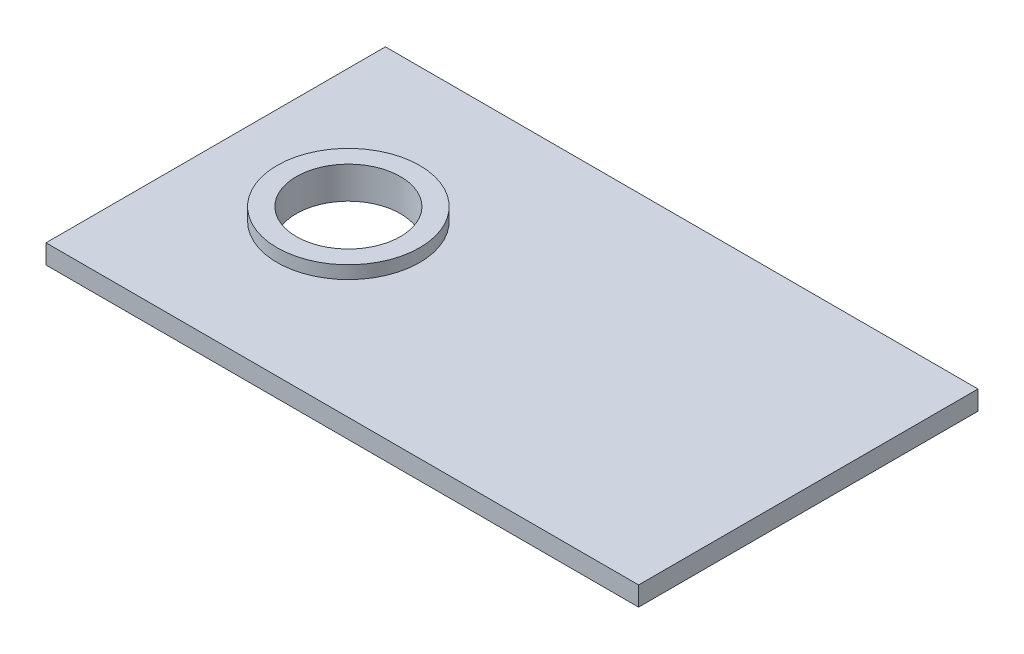
SolidWorks part; units mm, degrees
ref_plane "Front Plane" through (0, 0, 0) normal (0, 0, 1) x (1, 0, 0)
ref_plane "Top Plane" through (0, 0, 0) normal (0, 1, 0) x (1, 0, 0)
ref_plane "Right Plane" through (0, 0, 0) normal (1, 0, 0) x (0, 0, -1)
sketch "Sketch1" plane through (0, 0, 0) normal (0, 1, 0) x (1, 0, 0)
  line L0 (0, 0) -> (-25089.3372, 0) construction
  line L1 (-46.1264, -26.4178) -> (46.1264, -26.4178)
  line L2 (-46.1264, -26.4178) -> (-46.1264, 26.4178)
  line L3 (-46.1264, 26.4178) -> (46.1264, 26.4178)
  line L4 (46.1264, -26.4178) -> (46.1264, 26.4178)
  line L5 (-46.1264, -26.4178) -> (46.1264, 26.4178) construction
  line L6 (-46.1264, 26.4178) -> (46.1264, -26.4178) construction
  circle A0 centre (-25.471, 0) radius 8.1
  point P0 (0, 0)
  dimension "D1" = 16.2
extrude "Boss-Extrude1" add sketch "Sketch1" along normal blind 3
sketch "Sketch2" plane through (0, 3, 0) normal (0, 1, 0) x (1, 0, 0)
  line L0 (0, 0) -> (50000, 0) construction
  circle A0 centre (-25.471, 0) radius 8.1
  circle A1 centre (-25.471, 0) radius 11.1
  dimension "D1" = 3
extrude "Boss-Extrude2" add sketch "Sketch2" along normal blind 2
